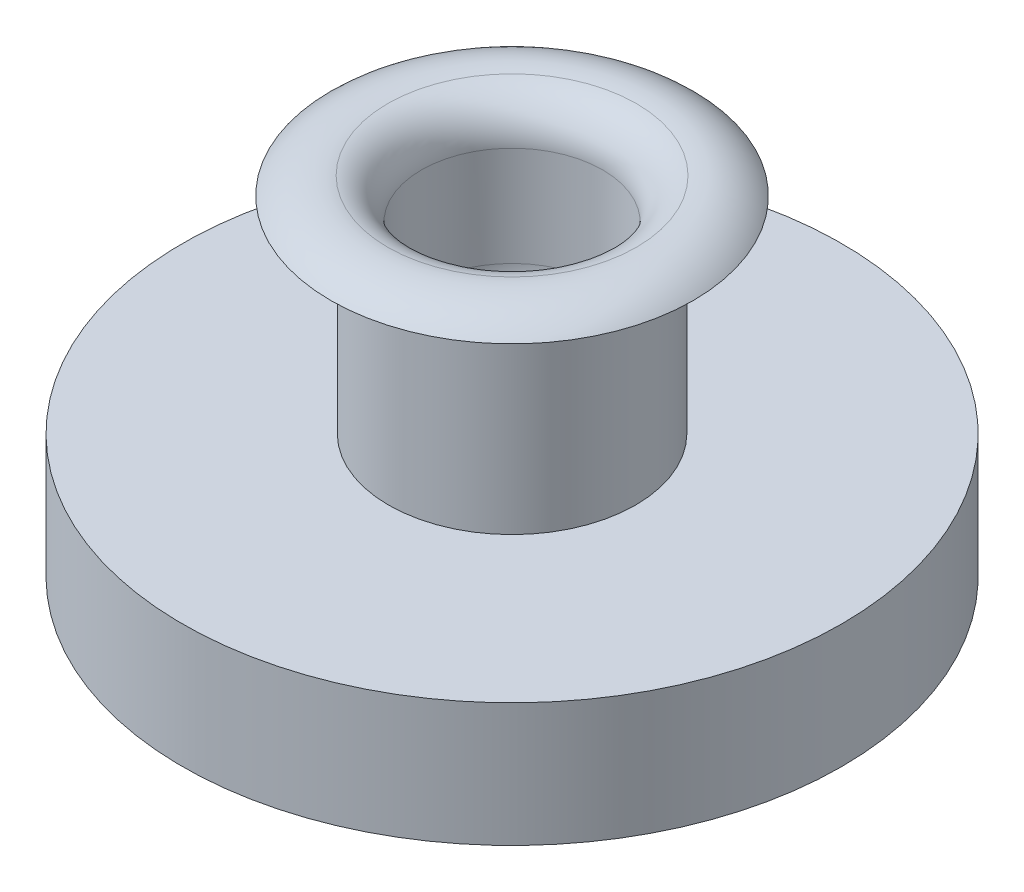
SolidWorks part; units mm, degrees
ref_plane "前视基准面" through (0, 0, 0) normal (0, 0, 1) x (1, 0, 0)
ref_plane "上视基准面" through (0, 0, 0) normal (0, 1, 0) x (1, 0, 0)
ref_plane "右视基准面" through (0, 0, 0) normal (1, 0, 0) x (0, 0, -1)
sketch "Sketch1" plane through (0, 0, 0) normal (0, 0, 1) x (1, 0, 0)
  line L0 (-1.5, 1) -> (-2.2, 1)
  line L1 (0, -1.5) -> (-1.5, -1.5)
  line L2 (0, -1.5) -> (0, 1) construction
  line L3 (0, 1) -> (-1.5, 1) construction
  line L4 (-1.5, -1.5) -> (-1.5, 1)
  line L5 (-1.1, 1) -> (-1.1, -1.1783)
  line L6 (-1.1, -1.1783) -> (0, -1.3412)
  line L7 (0, -1.3412) -> (0, -1.5)
  line L8 (0, 0.7121) -> (-1.1, 0.7121) construction
  arc A0 (-2.2, 1) -> (-1.1, 1) centre (-1.65, 0.4495) cw
revolve "Revolve1" add sketch "Sketch1" angle 360 about L2
fillet "Fillet1" radius 0.8 1 edges at (1.1, -1.1783, 0)
fillet "Fillet2" radius 0.5 1 edges at (1.1, 1, 0)
sketch "Sketch2" plane through (0, -1.5, 0) normal (0, -1, 0) x (1, 0, 0)
  circle A0 centre (0, 0) radius 4
extrude "Boss-Extrude1" add sketch "Sketch2" along normal blind 1.5
